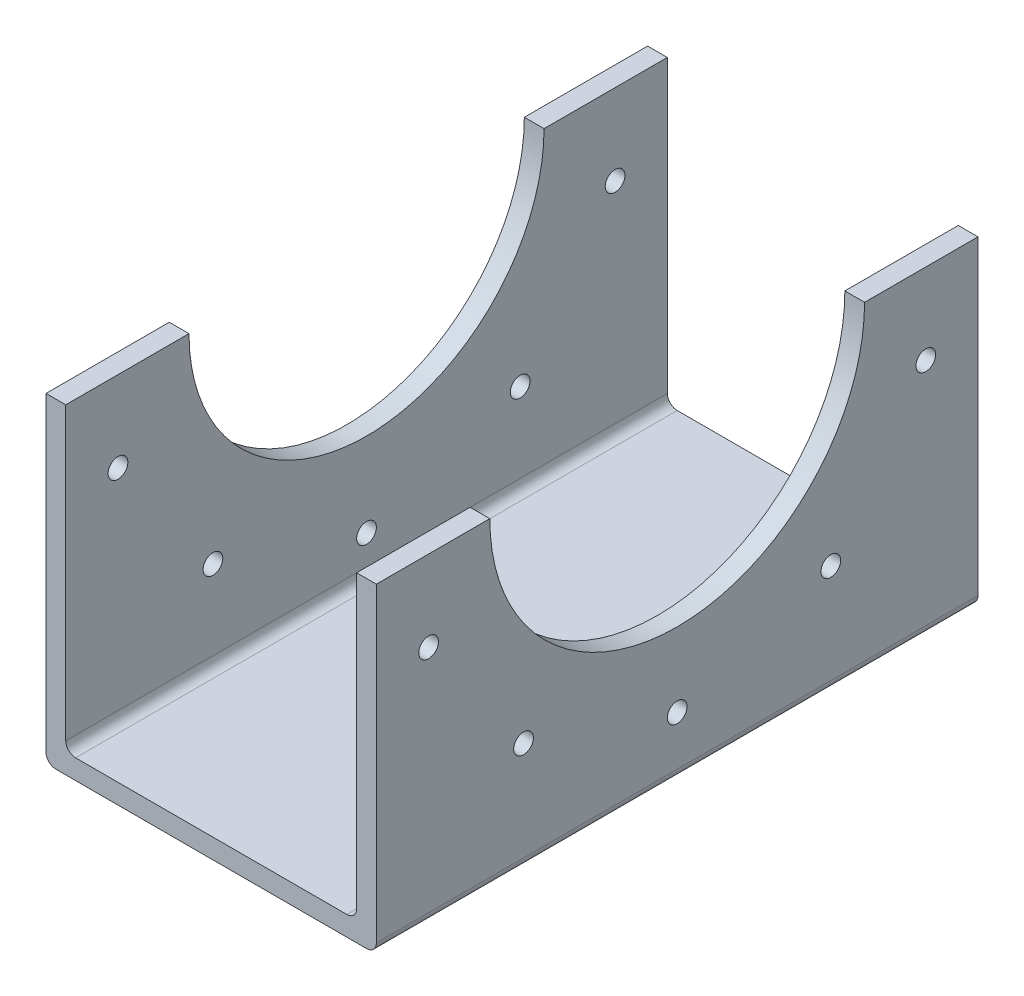
SolidWorks part; units mm, degrees
material "1060-H18"
ref_plane "Спереди" through (0, 0, 0) normal (0, 0, 1) x (1, 0, 0)
ref_plane "Сверху" through (0, 0, 0) normal (0, 1, 0) x (1, 0, 0)
ref_plane "Справа" through (0, 0, 0) normal (1, 0, 0) x (0, 0, -1)
other "Configuration Table"
sketch "Эскиз1" plane through (0, 0, 0) normal (0, 1, 0) x (1, 0, 0)
  line L1 (33.5, -61) -> (-33.5, -61)
  line L2 (33.5, -61) -> (33.5, 61)
  line L3 (33.5, 61) -> (-33.5, 61)
  line L4 (-33.5, -61) -> (-33.5, 61)
  line L5 (33.5, -61) -> (-33.5, 61) construction
  line L6 (33.5, 61) -> (-33.5, -61) construction
  point P0 (0, 0)
  point P8 (0, 16.5229)
  point P10 (0, 0)
  dimension "D1" = 122
  dimension "D2" = 67
extrude "Бобышка-Вытянуть1" add sketch "Эскиз1" along normal blind 4
sketch "Эскиз2" plane through (0, 4, 0) normal (0, 1, 0) x (1, 0, 0)
  line L0 (-33.5, -61) -> (33.5, -61) construction
  line L1 (-33.5, 61) -> (-29.5, 61)
  line L2 (-33.5, 61) -> (-33.5, -61)
  line L3 (-33.5, -61) -> (-29.5, -61)
  line L4 (-29.5, 61) -> (-29.5, -61)
  line L6 (33.5, 61) -> (29.5, 61)
  line L7 (33.5, 61) -> (33.5, -61)
  line L8 (33.5, -61) -> (29.5, -61)
  line L9 (29.5, 61) -> (29.5, -61)
  dimension "D1" = 4
  dimension "D2" = 4
extrude "Бобышка-Вытянуть2" add sketch "Эскиз2" along normal blind 61
fillet "Скругление1" radius 2 4 edges at (-29.5, 4, 0) (29.5, 4, 0) (-33.5, 0, 0) (33.5, 0, 0)
sketch "Эскиз4" plane through (33.5, 0, 0) normal (1, 0, 0) x (0, 0, -1)
  line L1 (-61, 65) -> (61, 65) construction
  line L2 (0, 65) -> (0, 12) construction
  circle A0 centre (0, 65) radius 38
  circle A1 centre (0, 65) radius 53 construction
  circle A2 centre (0, 12) radius 2
  circle A3 centre (-31.1526, 22.1221) radius 2
  circle A4 centre (0, 65) radius 53 construction
  circle A5 centre (-50.406, 48.6221) radius 2
  circle A6 centre (0, 65) radius 53 construction
  circle A7 centre (-50.406, 81.3779) radius 2 construction
  circle A8 centre (0, 65) radius 53 construction
  circle A9 centre (-31.1526, 107.8779) radius 2 construction
  circle A10 centre (0, 65) radius 53 construction
  circle A11 centre (0, 118) radius 2 construction
  circle A12 centre (0, 65) radius 53 construction
  circle A13 centre (31.1526, 107.8779) radius 2 construction
  circle A14 centre (0, 65) radius 53 construction
  circle A15 centre (50.406, 81.3779) radius 2 construction
  circle A16 centre (0, 65) radius 53 construction
  circle A17 centre (50.406, 48.6221) radius 2
  circle A18 centre (0, 65) radius 53 construction
  circle A19 centre (31.1526, 22.1221) radius 2
  circle A20 centre (0, 65) radius 53 construction
  point P4 (0, 0)
  point P10 (0, 65)
  dimension "D1" = 76
  dimension "D3" = 106
  dimension "D4" = 4
  dimension "D5" = 10
extrude "Вырез-Вытянуть1" cut sketch "Эскиз4" against normal blind 11
sketch "Эскиз5" plane through (-33.5, 0, 0) normal (-1, 0, 0) x (0, 0, 1)
  line L0 (0, 65) -> (0, 12) construction
  line L1 (-61, 65) -> (61, 65) construction
  circle A0 centre (0, 65) radius 36
  circle A1 centre (0, 65) radius 53 construction
  circle A2 centre (0, 12) radius 2
  circle A3 centre (-31.1526, 22.1221) radius 2
  circle A4 centre (0, 65) radius 53 construction
  circle A5 centre (-50.406, 48.6221) radius 2
  circle A6 centre (0, 65) radius 53 construction
  circle A7 centre (-50.406, 81.3779) radius 2 construction
  circle A8 centre (0, 65) radius 53 construction
  circle A9 centre (-31.1526, 107.8779) radius 2 construction
  circle A10 centre (0, 65) radius 53 construction
  circle A11 centre (0, 118) radius 2 construction
  circle A12 centre (0, 65) radius 53 construction
  circle A13 centre (31.1526, 107.8779) radius 2 construction
  circle A14 centre (0, 65) radius 53 construction
  circle A15 centre (50.406, 81.3779) radius 2 construction
  circle A16 centre (0, 65) radius 53 construction
  circle A17 centre (50.406, 48.6221) radius 2
  circle A18 centre (0, 65) radius 53 construction
  circle A19 centre (31.1526, 22.1221) radius 2
  circle A20 centre (0, 65) radius 53 construction
  point P3 (0, 65)
  point P8 (0, 0)
  dimension "D1" = 72
  dimension "D3" = 106
  dimension "D4" = 4
  dimension "D5" = 10
extrude "Вырез-Вытянуть2" cut sketch "Эскиз5" against normal blind 11 contours A0 | A5 | A3 | A19 | A17 | A2
equation "\"D2@Эскиз2\"=\"D1@Эскиз2\""
